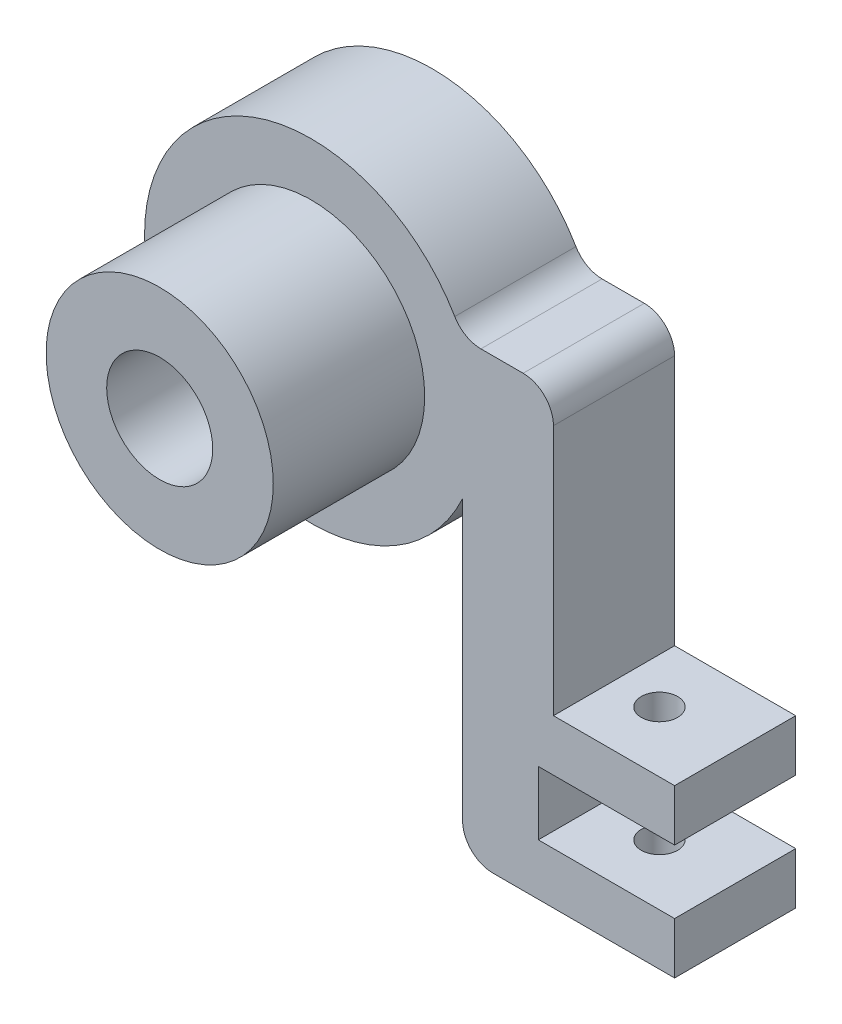
SolidWorks part; units mm, degrees
ref_plane "Plan de face" through (0, 0, 0) normal (0, 0, 1) x (1, 0, 0)
ref_plane "Plan de dessus" through (0, 0, 0) normal (0, 1, 0) x (1, 0, 0)
ref_plane "Plan de droite" through (0, 0, 0) normal (1, 0, 0) x (0, 0, -1)
sketch "Esquisse1" plane through (0, 0, 0) normal (0, 0, 1) x (1, 0, 0)
  line L1 (0, 0) -> (35, 0) construction
  line L2 (0, 0) -> (0, -36) construction
  line L3 (0, -36) -> (35, -36) construction
  line L4 (35, 0) -> (35, -36) construction
  line L5 (21, -6.4174) -> (27, -6.4174)
  line L7 (27, -6.4174) -> (27, -25)
  line L8 (35, -28.4) -> (35, -25)
  line L9 (35, -36) -> (21, -36)
  line L10 (35, -36) -> (35, -32.6)
  line L11 (35, -25) -> (27, -25)
  line L14 (21, -36) -> (21, -15.5826)
  line L17 (35, -32.6) -> (26, -32.6)
  line L19 (35, -28.4) -> (26, -28.4)
  line L20 (26, -32.6) -> (26, -28.4)
  line L21 (21, -6.4174) -> (21, -15.5826) construction
  arc A0 (21, -6.4174) -> (21, -15.5826) centre (11, -11) ccw
  point P6 (21, -11)
  point P20 (26, -30.5)
  dimension "D3" = 22
  dimension "D1" = 35
  dimension "D2" = 36
  dimension "D4" = 11
  dimension "D5" = 11
  dimension "D6" = 11
  dimension "D8" = 9
  dimension "D9" = 4.2
  dimension "D10" = 5.5
  dimension "D11" = 8
  dimension "D7" = 21
extrude "Boss.-Extru.1" add sketch "Esquisse1" along normal blind 8
sketch "Esquisse2" plane through (0, -25, 0) normal (0, 1, 0) x (1, 0, 0)
  line L0 (27, -8) -> (27, 0) construction
  line L1 (35, -8) -> (27, -8) construction
  circle A0 centre (30, -4) radius 1
  dimension "D1" = 2
  dimension "D2" = 3
  dimension "D3" = 4
extrude "Enlèv. mat.-Extru.1" cut sketch "Esquisse2" against normal up to surface (11 mm away) up to face at (28, -36, 4)
hole_wizard "Dégagement M21" positions "Esquisse3" profile "Esquisse4" hole size "M2" standard "ISO"
sketch "Esquisse3" plane through (0, -25, 0) normal (0, 1, 0) x (1, 0, 0)
  point P0 (30, -4)
sketch "Esquisse4" plane through (30, -25, 4) normal (1, 0, 0) x (0, 0, 1)
  line L0 (0, 0) -> (0, 11.721)
  line L1 (0, 11.721) -> (1.2, 11)
  line L2 (1.2, 11) -> (1.2, 0)
  line L5 (1.2, 0) -> (0, 0)
  line L10 (0, 11.721) -> (-1.2, 11) construction
  line L11 (0, -6.35) -> (0, 107.95) construction
  dimension "Diamètre du perçage" = 2.4
  dimension "Profondeur du perçage" = 11
  dimension "Angle de pointe" = 118
fillet "Congé1" radius 2 3 edges at (21, -36, 4) (21, -6.4174, 4) (27, -6.4174, 4)
sketch "Esquisse5" plane through (0, 0, 8) normal (0, 0, 1) x (1, 0, 0)
  circle A0 centre (11, -11) radius 7.5
  dimension "D1" = 15
extrude "Boss.-Extru.2" add sketch "Esquisse5" along normal blind 10
sketch "Esquisse6" plane through (0, 0, 0) normal (0, 0, -1) x (-1, 0, 0)
  line L0 (-11, -3.5) -> (-11, -18.5) construction
  line L1 (0, -4.0566) -> (0, -19.2348) construction
  line L2 (-19.6078, 0) -> (-3.8534, 0) construction
  circle A0 centre (-11, -3.5) radius 1
  circle A1 centre (-11, -18.5) radius 1
  arc A2 (-21, -15.5826) -> (-20.4856, -5.4301) centre (-11, -11) ccw construction
  circle A3 centre (-11, -11) radius 3.5 construction
  point P8 (-11, -11)
  dimension "D2" = 2
  dimension "D3" = 2
  dimension "D5" = 7
  dimension "D1" = 11
  dimension "D4" = 11
  dimension "D6" = 15
extrude "Enlèv. mat.-Extru.2" cut sketch "Esquisse6" against normal offset from surface (6 mm away) 2 up to face at (18.5, -11, 8)
sketch "Esquisse8" plane through (0, 0, 0) normal (0, 0, -1) x (-1, 0, 0)
  circle A0 centre (-11, -11) radius 3.5
  dimension "D1" = 7
extrude "Enlèv. mat.-Extru.3" cut sketch "Esquisse8" against normal up to surface (18 mm away) up to face at (18.5, -11, 18)
equation "\"D4@Esquisse1\"=\"D3@Esquisse1\"/2"
equation "\"D5@Esquisse1\"=\"D3@Esquisse1\"/2"
equation "\"D10@Esquisse1\"=\"D6@Esquisse1\"/2"
